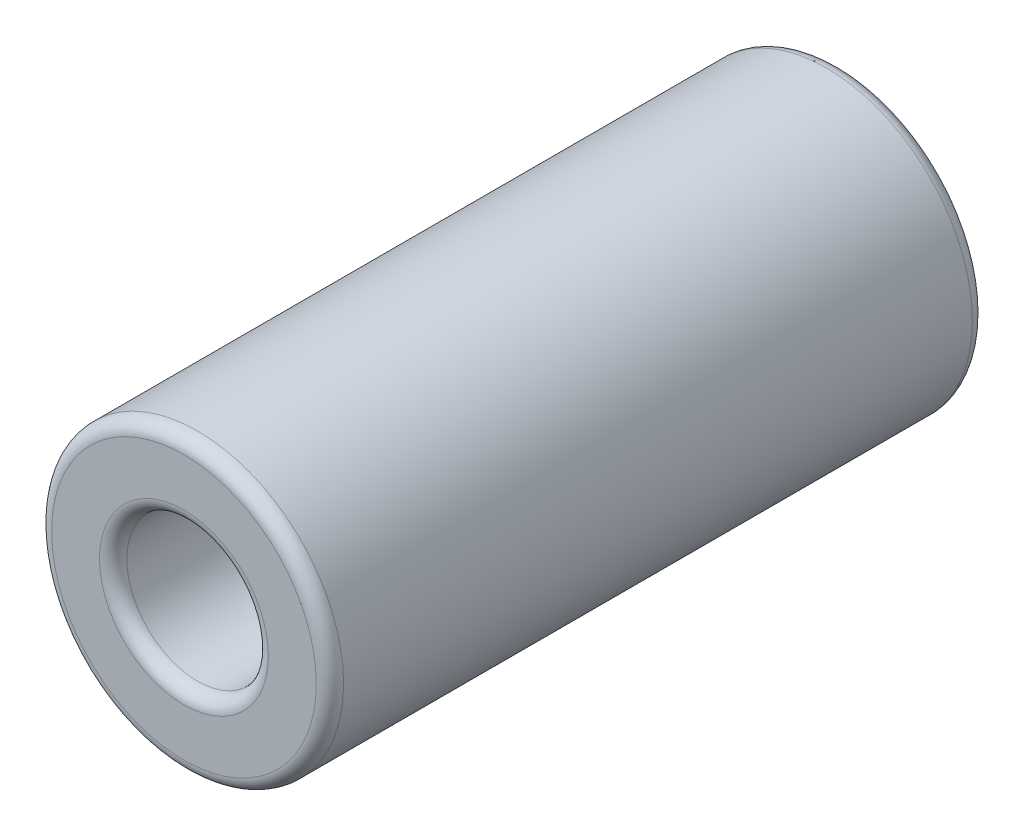
SolidWorks part; units mm, degrees
material "Медь"
ref_plane "Спереди" through (0, 0, 0) normal (0, 0, 1) x (1, 0, 0)
ref_plane "Сверху" through (0, 0, 0) normal (0, 1, 0) x (1, 0, 0)
ref_plane "Справа" through (0, 0, 0) normal (1, 0, 0) x (0, 0, -1)
sketch "Эскиз1" plane through (0, 0, 0) normal (0, 0, 1) x (1, 0, 0)
  circle A0 centre (0, 0) radius 3.625
  circle A1 centre (0, 0) radius 7.475
  dimension "D1" = 7.25
  dimension "D2" = 14.95
extrude "Вытянуть1" add sketch "Эскиз1" along normal blind 33.6
fillet "Скругление1" radius 0.7 4 edges at (3.625, 0, 0) (7.475, 0, 0) (3.625, 0, 33.6) (7.475, 0, 33.6)
